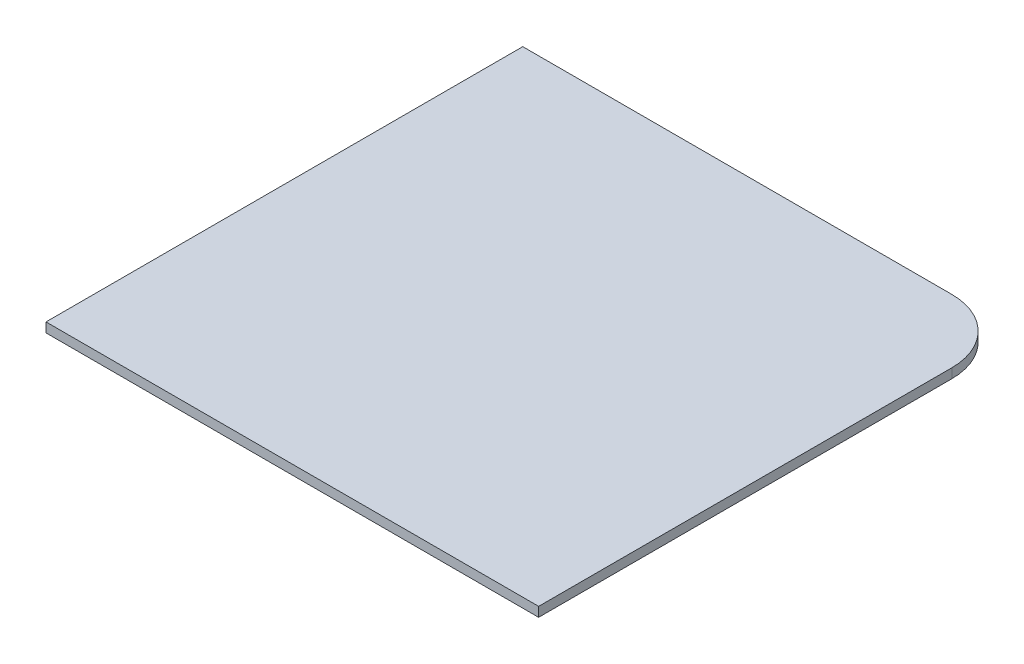
SolidWorks part; units mm, degrees
ref_plane "Front Plane" through (0, 0, 0) normal (0, 0, 1) x (1, 0, 0)
ref_plane "Top Plane" through (0, 0, 0) normal (0, 1, 0) x (1, 0, 0)
ref_plane "Right Plane" through (0, 0, 0) normal (1, 0, 0) x (0, 0, -1)
sketch "Sketch1" plane through (0, 0, 0) normal (0, 1, 0) x (1, 0, 0)
  line L2 (-77.5, 75) -> (-77.5, -75)
  line L3 (-77.5, -75) -> (77.5, -75)
  line L5 (-55, 0) -> (55, 0) construction
  line L6 (0, -55) -> (0, 55) construction
  line L7 (77.5, -75) -> (77.5, 55)
  line L8 (57.5, 75) -> (-77.5, 75)
  arc A0 (77.5, 55) -> (57.5, 75) centre (57.5, 55) ccw
  point P4 (-77.5, 0)
  point P7 (0, -75)
  dimension "D3" = 20
  dimension "D1" = 155
  dimension "D2" = 150
extrude "Boss-Extrude1" add sketch "Sketch1" along normal blind 3
